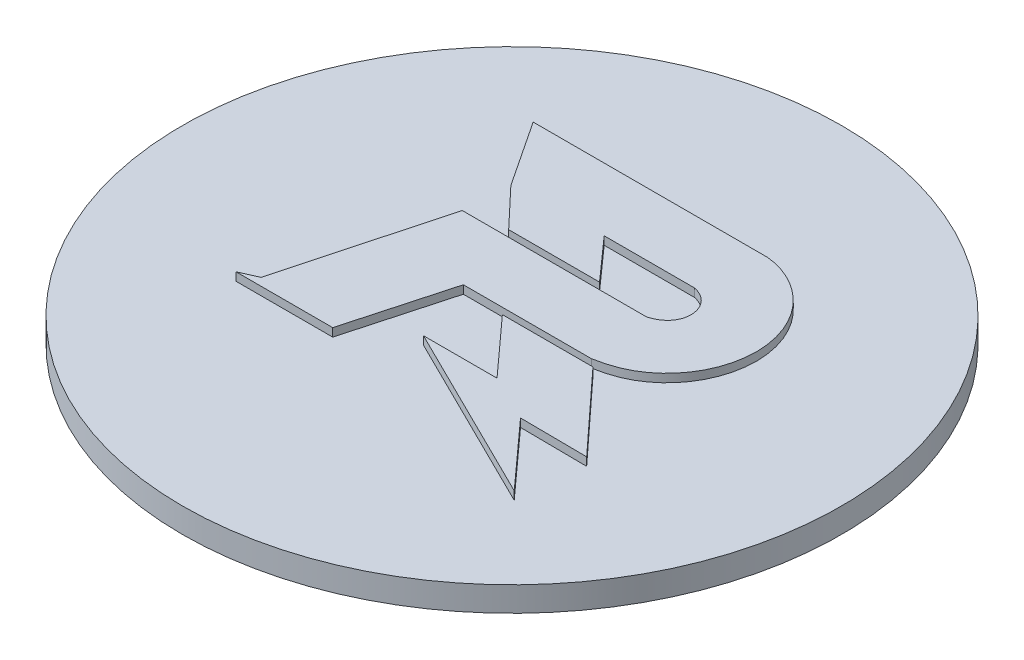
SolidWorks part; units mm, degrees
ref_plane "前视基准面" through (0, 0, 0) normal (0, 0, 1) x (1, 0, 0)
ref_plane "上视基准面" through (0, 0, 0) normal (0, 1, 0) x (1, 0, 0)
ref_plane "右视基准面" through (0, 0, 0) normal (1, 0, 0) x (0, 0, -1)
other "Configuration Table"
sketch "草图1" plane through (0, 0, 0) normal (0, 1, 0) x (1, 0, 0)
  line L0 (66.1667, 196.5) -> (330.8333, 196.5) construction
  line L1 (0, 79.194) -> (3.8287, 78.9924)
  line L2 (23.3753, 53.602) -> (45.4268, 53.602)
  line L3 (45.4268, 53.602) -> (36.2625, 63.9046)
  line L4 (36.2625, 63.9046) -> (58.8248, 63.9046)
  line L5 (58.4703, 51.9899) -> (13.7028, 51.9899)
  line L6 (13.7028, 51.9899) -> (3.3741, 13.5336)
  line L7 (3.3741, 13.5336) -> (0, 12.0289)
  line L8 (0, 12.0289) -> (0, 79.194)
  line L9 (60.6549, 79.194) -> (79.7985, 77.9849)
  line L10 (79.7985, 77.9849) -> (79.9901, 15.9717)
  line L11 (79.9901, 15.9717) -> (62.4673, 34.9685)
  line L12 (62.4673, 34.9685) -> (40.4775, 34.9685)
  line L13 (40.4775, 34.9685) -> (53.1931, 20.961)
  line L14 (53.1931, 20.961) -> (35.3408, 20.961)
  line L15 (35.3408, 20.961) -> (77.6929, 0)
  line L16 (77.6929, 0) -> (0, 0)
  line L17 (0, 0) -> (0, 11.6505)
  line L18 (0, 11.6505) -> (22.6178, 11.6505)
  line L19 (22.6178, 11.6505) -> (29.4584, 36.5217)
  line L20 (29.4584, 36.5217) -> (60.5085, 36.5217)
  line L21 (64.2192, 15.4559) -> (79.7985, 15.3149)
  line L22 (79.7985, 15.3149) -> (79.7985, 0)
  spline S0 degree 3 poles (3.8287, 78.9924) (4.8559, 76.9381) (6.3807, 75.0637) (7.6574, 73.1486) (8.7322, 71.5365) (9.8069, 69.9244) (11.9563, 66.7003) (12.9163, 65.0054) (14.1058, 63.4761) (14.4557, 63.0262) (14.9235, 62.6814) (15.3149, 62.267) (18.0254, 59.397) (20.5829, 56.3945) (23.3753, 53.602) knots 0 0 0 0 1 1 1 2 2 3 3 3 4 4 4 5 5 5 5
  spline S1 degree 3 poles (58.8248, 63.9046) (59.292, 63.5431) (59.8964, 63.6295) (60.3636, 63.268) (61.0567, 62.7316) (61.8327, 62.288) (62.443, 61.659) (62.9283, 61.1589) (63.5088, 59.8334) (63.6023, 59.0998) (63.7767, 57.733) (63.8648, 56.2946) (63.0744, 55.076) (61.8408, 53.1741) (60.5044, 52.6736) (58.4703, 51.9899) knots 0 0 0 0 1 1 1 2 2 2 3 3 3 4 4 4 5 5 5 5
  spline S2 degree 3 poles (60.5085, 36.5217) (64.3346, 38.9945) (69.1027, 40.4137) (71.9868, 43.9401) (74.8776, 47.4746) (76.6948, 52.1317) (77.0014, 56.6874) (77.3032, 61.1725) (76.1444, 65.9804) (73.725, 69.769) (69.0247, 77.1293) (66.2784, 77.575) (60.6549, 79.194) knots 0 0 0 0 1 1 1 2 2 2 3 3 3 4 4 4 4
  spline S3 degree 3 poles (79.7985, 0) (79.2618, 0.072) (78.6361, -0.0884) (78.1883, 0.216) (77.3625, 0.7774) (76.8627, 1.7098) (76.1932, 2.4507) (72.2454, 6.8201) (68.3456, 11.2545) (64.2192, 15.4559) knots 0 0 0 0 1 1 1 2 2 2 3 3 3 3
  point P28 (45.4268, 53.602)
  point P29 (36.2625, 63.9046)
  point P30 (58.8248, 63.9046)
  point P31 (58.4703, 51.9899)
  point P32 (29.4584, 36.5217)
  point P33 (0, 11.6505)
  point P34 (0, 0)
  point P36 (22.6178, 11.6505)
  point P37 (0, 12.0289)
  point P38 (3.3741, 13.5336)
  point P39 (40.4775, 34.9685)
  point P40 (53.1931, 20.961)
  point P41 (35.3408, 20.961)
  point P42 (77.6929, 0.2015)
  point P43 (79.8952, 0)
  point P44 (63.9113, 15.4586)
  point P45 (79.7985, 0)
  point P46 (79.9901, 15.9717)
  point P47 (62.4673, 34.9685)
  point P48 (60.5085, 36.5217)
sketch "草图3" plane through (0, 0, 0) normal (0, 1, 0) x (1, 0, 0)
  line L0 (64.4003, 15.4542) -> (78.9476, -0.621)
  line L1 (77.6929, 0) -> (78.9476, -0.621)
  line L2 (79.7985, 15.3149) -> (64.2192, 15.4559)
  line L3 (79.7985, 0) -> (79.7985, 15.3149)
  line L4 (80.6027, 15.3076) -> (64.4003, 15.4542)
  line L6 (64.2192, 15.4559) -> (79.7985, 15.3149) construction
  line L7 (58.4703, 51.9899) -> (60.9014, 52.8) construction
  line L8 (3.8287, 78.9924) -> (0, 79.194)
  line L9 (45.4268, 53.602) -> (23.3753, 53.602)
  line L10 (36.2625, 63.9046) -> (45.4268, 53.602)
  line L11 (58.8248, 63.9046) -> (36.2625, 63.9046)
  line L12 (13.7028, 51.9899) -> (58.4703, 51.9899)
  line L13 (3.3741, 13.5336) -> (13.7028, 51.9899)
  line L14 (0, 12.0289) -> (3.3741, 13.5336)
  line L15 (0, 79.194) -> (0, 12.0289)
  line L17 (45.4268, 53.602) -> (23.3753, 53.602)
  line L18 (36.2625, 63.9046) -> (45.4268, 53.602)
  line L19 (58.1617, 63.9046) -> (36.2625, 63.9046)
  line L20 (13.7028, 51.9899) -> (58.4703, 51.9899)
  line L21 (3.3741, 13.5336) -> (13.7028, 51.9899)
  line L22 (-0.8486, 11.6505) -> (3.3741, 13.5336)
  line L24 (60.9014, 52.8) -> (65.3288, 54.3726) construction
  line L25 (65.3288, 54.3726) -> (64.8831, 61.2447) construction
  line L26 (64.8831, 61.2447) -> (61.1305, 63.2852) construction
  line L27 (61.1305, 63.2852) -> (58.1617, 63.9046) construction
  line L28 (36.2625, 63.9046) -> (58.8248, 63.9046) construction
  line L29 (60.5085, 36.5217) -> (64.7215, 37.3146) construction
  line L30 (64.7215, 37.3146) -> (69.4859, 38.6758) construction
  line L31 (69.4859, 38.6758) -> (74.6472, 40.9333) construction
  line L32 (53.1931, 20.961) -> (40.4775, 34.9685)
  line L33 (35.3408, 20.961) -> (53.1931, 20.961)
  line L34 (77.6929, 0) -> (35.3408, 20.961)
  line L35 (0, 0) -> (77.6929, 0)
  line L36 (0, 11.6505) -> (0, 0)
  line L37 (22.6178, 11.6505) -> (0, 11.6505)
  line L38 (29.4584, 36.5217) -> (22.6178, 11.6505)
  line L39 (60.5085, 36.5217) -> (29.4584, 36.5217)
  line L40 (79.7985, 77.9849) -> (60.6549, 79.194)
  line L41 (79.9901, 15.9717) -> (79.7985, 77.9849)
  line L42 (62.4673, 34.9685) -> (79.9901, 15.9717)
  line L43 (40.4775, 34.9685) -> (62.4673, 34.9685)
  line L44 (53.1931, 20.961) -> (40.4775, 34.9685)
  line L45 (35.3408, 20.961) -> (53.1931, 20.961)
  line L46 (77.6929, 0) -> (35.3408, 20.961)
  line L49 (22.6178, 11.6505) -> (-0.8486, 11.6505)
  line L50 (29.4584, 36.5217) -> (22.6178, 11.6505)
  line L51 (60.5085, 36.5217) -> (29.4584, 36.5217)
  line L54 (62.4673, 34.9685) -> (80.6027, 15.3076)
  line L55 (40.4775, 34.9685) -> (62.4673, 34.9685)
  line L56 (74.6472, 40.9333) -> (83.8736, 49.7542) construction
  line L58 (83.8736, 49.7542) -> (83.8248, 60.6045) construction
  line L59 (83.8248, 60.6045) -> (79.1459, 72.2096) construction
  line L60 (79.1459, 72.2096) -> (71.7191, 73.8449) construction
  line L62 (71.7191, 73.8449) -> (68.9052, 78.4299) construction
  line L63 (68.9052, 78.4299) -> (60.6549, 79.194) construction
  line L64 (60.6549, 79.194) -> (3.7299, 79.194)
  line L65 (3.7299, 79.194) -> (14.3494, 63.1598)
  line L66 (23.3753, 53.602) -> (14.3494, 63.1598)
  spline_without_curve S0
  spline S1 degree 3 poles (-763.2996, -545.9799) (-22.9254, 134.2629) (22.1423, 62.2746) (76.1932, 2.4507) (76.8627, 1.7098) (77.3625, 0.7774) (78.1883, 0.216) (83.4346, -3.3502) (113.0697, 56.8719) (-261.4424, -939.9465) knots -12.691467 -12.691467 -12.691467 -12.691467 1 1 1 2 2 2 13.714031 13.714031 13.714031 13.714031 only from (64.2192, 15.4559) to (79.7985, 0)
  spline S2 degree 3 poles (857.4229, 605.2886) (59.6268, -32.9088) (50.0029, 25.5384) (15.3149, 62.267) (14.9235, 62.6814) (14.4557, 63.0262) (14.1058, 63.4761) (12.9163, 65.0054) (11.9563, 66.7003) (9.8069, 69.9244) (8.7322, 71.5365) (7.6574, 73.1486) (-6.73, 94.7297) (-52.6191, 111.1409) (937.1267, 438.0736) knots -11.797565 -11.797565 -11.797565 -11.797565 1 1 1 2 2 2 3 3 4 4 4 15.268811 15.268811 15.268811 15.268811 only from (23.3753, 53.602) to (3.8287, 78.9924)
  spline S3 degree 3 poles (-432.7687, -819.0265) (32.431, 134.9077) (51.9405, 37.9101) (63.0744, 55.076) (63.8648, 56.2946) (63.7767, 57.733) (63.6023, 59.0998) (63.5088, 59.8334) (62.9283, 61.1589) (62.443, 61.659) (61.8327, 62.288) (61.0567, 62.7316) (60.3636, 63.268) (55.3538, 67.1444) (34.584, 19.5232) (336.0049, 1024.7055) knots -8.025538 -8.025538 -8.025538 -8.025538 1 1 1 2 2 2 3 3 3 4 4 4 14.72187 14.72187 14.72187 14.72187 only from (58.4703, 51.9899) to (58.8248, 63.9046)
  spline_without_curve S5
  spline S7 degree 3 poles (-582.6926, 844.7592) (79.641, -50.8353) (48.464, 109.3258) (73.725, 69.769) (76.1444, 65.9804) (77.3032, 61.1725) (77.0014, 56.6874) (76.6948, 52.1317) (74.8776, 47.4746) (71.9868, 43.9401) (52.1395, 19.673) (-56.9231, 95.1952) (665.7085, -759.5512) knots -4.374358 -4.374358 -4.374358 -4.374358 1 1 1 2 2 2 3 3 3 9.88155 9.88155 9.88155 9.88155 only from (60.6549, 79.194) to (60.5085, 36.5217)
  point P12 (0, 0)
  point P38 (-2.062, 11.6505)
  point P43 (-0.8446, 11.6505)
  point P45 (-0.7732, 11.6505)
  point P46 (-0.8801, 11.6505)
  dimension "D1" = 0
  dimension "D2" = 0
  dimension "D3" = 0
sketch "草图5" plane through (0, 0, 0) normal (0, 1, 0) x (1, 0, 0)
  line L24 (-0.8486, 11.6505) -> (10.8846, 11.6505)
  line L25 (10.8846, 11.6505) -> (14.3049, 24.0861)
  line L26 (14.3049, 24.0861) -> (29.83, 24.0861)
  line L27 (29.9032, 45.4222) -> (1.4407, 45.4222)
  line L28 (1.4407, 45.4222) -> (6.7504, 37.4052)
  line L29 (6.7504, 37.4052) -> (11.2634, 32.6263)
  line L30 (11.2634, 32.6263) -> (22.2891, 32.6263)
  line L31 (22.2891, 32.6263) -> (17.707, 37.7776)
  line L32 (17.707, 37.7776) -> (28.6566, 37.7776)
  line L33 (28.8109, 31.8202) -> (6.4271, 31.8202)
  line L34 (6.4271, 31.8202) -> (1.2628, 12.5921)
  line L35 (1.2628, 12.5921) -> (-0.8486, 11.6505)
  line L40 (39.8771, 13.4791) -> (30.8094, 23.3095)
  line L41 (30.8094, 23.3095) -> (19.8145, 23.3095)
  line L42 (19.8145, 23.3095) -> (26.1723, 16.3057)
  line L43 (26.1723, 16.3057) -> (17.2461, 16.3057)
  line L44 (17.2461, 16.3057) -> (38.4222, 5.8253)
  line L45 (38.4222, 5.8253) -> (39.0495, 5.5148)
  line L46 (39.0495, 5.5148) -> (31.7759, 13.5524)
  line L47 (31.7759, 13.5524) -> (39.8771, 13.4791)
  spline S4 degree 9 poles (29.83, 24.0861) (31.9365, 24.4826) (34.3187, 25.1632) (36.8993, 26.2919) (41.5125, 30.7023) (41.4881, 36.1275) (39.1487, 41.9301) (35.4353, 42.7477) (34.0283, 45.0402) (29.9032, 45.4222) knots 0 0 0 0 0 0 0 0 0 0 1 1 1 1 1 1 1 1 1 1
  spline S5 degree 5 poles (28.6566, 37.7776) (30.1409, 37.4679) (32.0173, 36.4476) (32.2401, 33.0115) (30.0264, 32.2253) (28.8109, 31.8202) knots 0 0 0 0 0 0 1 1 1 1 1 1
sketch "草图6" plane through (0, 0, 0) normal (0, 1, 0) x (1, 0, 0)
  line L0 (-0.8486, 11.6505) -> (39.8771, 11.6505) construction
  line L1 (19.5143, 11.6505) -> (19.5143, 42.9662) construction
  circle A0 centre (19.5143, 24.7798) radius 40
  circle A1 centre (19.5143, 24.7798) radius 27.4366 construction
  dimension "D1" = 80
extrude "凸台-拉伸1" add sketch "草图6" against normal blind 3
extrude "凸台-拉伸2" add sketch "草图5" along normal blind 1
